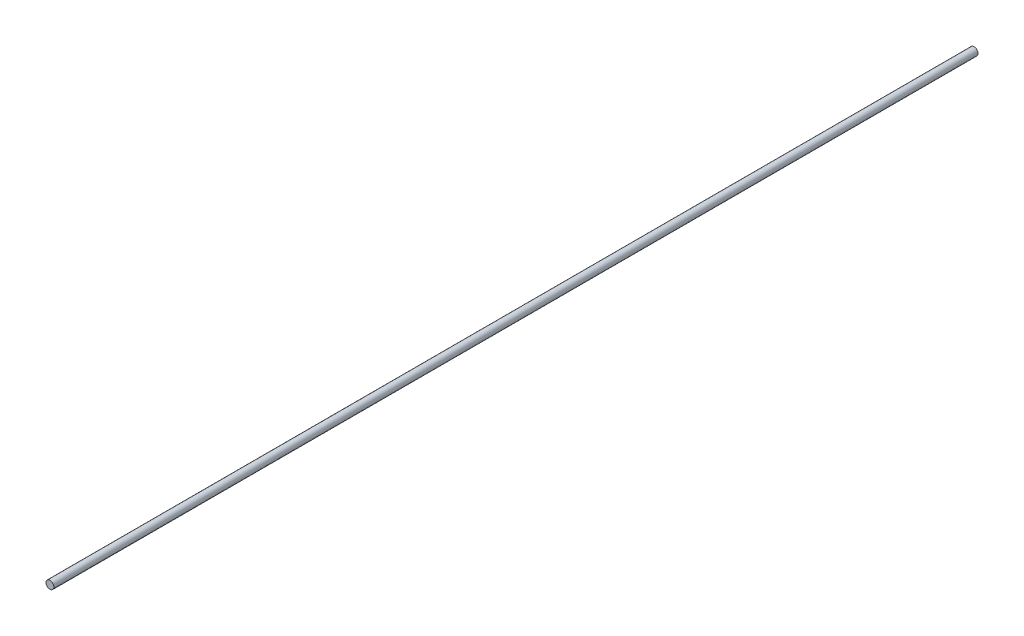
SolidWorks part; units mm, degrees
ref_plane "Ebene vorne" through (0, 0, 0) normal (0, 0, 1) x (1, 0, 0)
ref_plane "Ebene oben" through (0, 0, 0) normal (0, 1, 0) x (1, 0, 0)
ref_plane "Ebene rechts" through (0, 0, 0) normal (1, 0, 0) x (0, 0, -1)
sketch "Skizze1" plane through (0, 0, 0) normal (0, 0, 1) x (1, 0, 0)
  circle A0 centre (0, 0) radius 4
  dimension "D1" = 8
extrude "Aufsatz-Linear austragen1" add sketch "Skizze1" along normal blind 944.85
